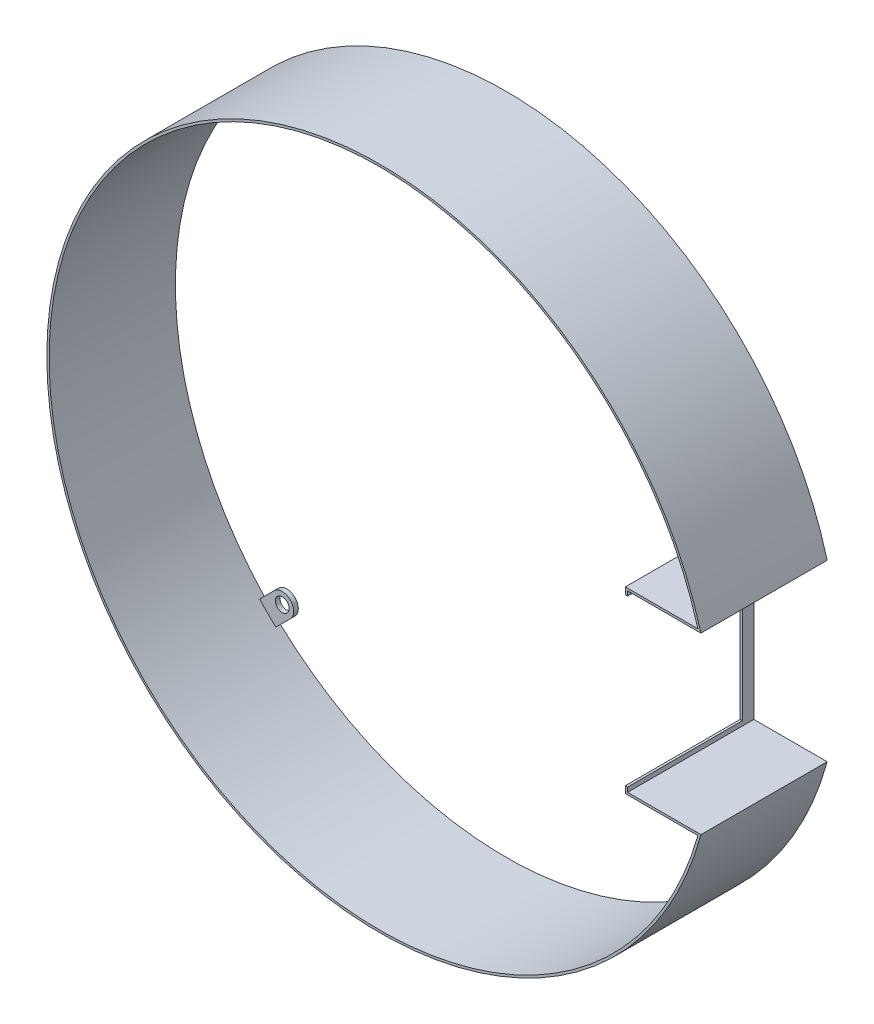
SolidWorks part; units mm, degrees
material "ABS"
ref_plane "Ebene vorne" through (0, 0, 0) normal (0, 0, 1) x (1, 0, 0)
ref_plane "Ebene oben" through (0, 0, 0) normal (0, 1, 0) x (1, 0, 0)
ref_plane "Ebene rechts" through (0, 0, 0) normal (1, 0, 0) x (0, 0, -1)
sketch "Skizze1" plane through (0, 0, 0) normal (0, 0, 1) x (1, 0, 0)
  line L0 (69.3091, 19.5) -> (53.5, 19.5)
  line L1 (53.5, 19.5) -> (53.5, 0)
  line L2 (53.5, 0) -> (54, 0)
  line L3 (54, 0) -> (54, 19)
  line L4 (54, 19) -> (69.9661, 19)
  line L5 (-72.5, 0) -> (-72, 0)
  line L6 (0, 0) -> (92.5823, 0) construction
  arc A0 (69.9661, 19) -> (-72.5, 0) centre (0, 0) ccw
  arc A1 (69.3091, 19.5) -> (-72, 0) centre (0, 0) ccw
  dimension "D1" = 0.5
  dimension "D2" = 72.5
  dimension "D3" = 0.5
  dimension "D4" = 0.5
  dimension "D5" = 39
  dimension "D6" = 54
extrude "Cover Base" add sketch "Skizze1" along normal blind 27.5
sketch "Skizze2" plane through (53.5, 0, 0) normal (1, 0, 0) x (0, 0, -1)
  line L0 (-27.5, 0) -> (-27.5, 19) construction
  line L1 (-27.5, 18) -> (-2.5, 18)
  line L2 (-27.5, 18) -> (-27.5, 0)
  line L3 (-27.5, 0) -> (-2.5, 0)
  line L4 (-2.5, 18) -> (-2.5, 0)
  line L5 (-27.5, 0) -> (0, 0) construction
  line L6 (0, 0) -> (0, 19) construction
  dimension "D1" = 18
  dimension "D2" = 2.5
extrude "Camera Cover Cut" cut sketch "Skizze2" along normal through all
mirror "Cover Mirror" about plane through (0, 0, 0) normal (0, 1, 0) of "Cover Base", "Camera Cover Cut"
sketch "Skizze3" plane through (0, 0, 0) normal (0, 0, 1) x (1, 0, 0)
  line L0 (0, 0) -> (51.2652, 51.2652) construction
  line L1 (0, 0) -> (86.3992, 0) construction
  line L3 (49.4975, 53.033) -> (45.9619, 49.4975)
  line L4 (45.9619, 49.4975) -> (49.4975, 45.9619) construction
  line L5 (49.4975, 45.9619) -> (53.033, 49.4975)
  line L6 (53.033, 49.4975) -> (49.4975, 53.033)
  circle A0 centre (0, 0) radius 67.5 construction
  arc A1 (69.9661, 19) -> (69.9661, -19) centre (0, 0) ccw construction
  circle A2 centre (49.4975, 49.4975) radius 2.5 construction
  arc A4 (45.9619, 49.4975) -> (49.4975, 45.9619) centre (47.7297, 47.7297) ccw
  circle A5 centre (0, 0) radius 72
  arc A6 (69.3091, 19.5) -> (69.3091, -19.5) centre (0, 0) ccw construction
  circle A7 centre (47.7297, 47.7297) radius 1.5
  dimension "D1" = 135
  dimension "D3" = 5
  dimension "D4" = 3
  dimension "D2" = 45
extrude "Spacer Screw" add sketch "Skizze3" along normal blind 1 contours L5 A5 L3 A4 A7
pattern_circular "Kreismuster1" count 4 over 360 about axis through (0, 0, 0) along (0, 0, 1) of "Spacer Screw"
